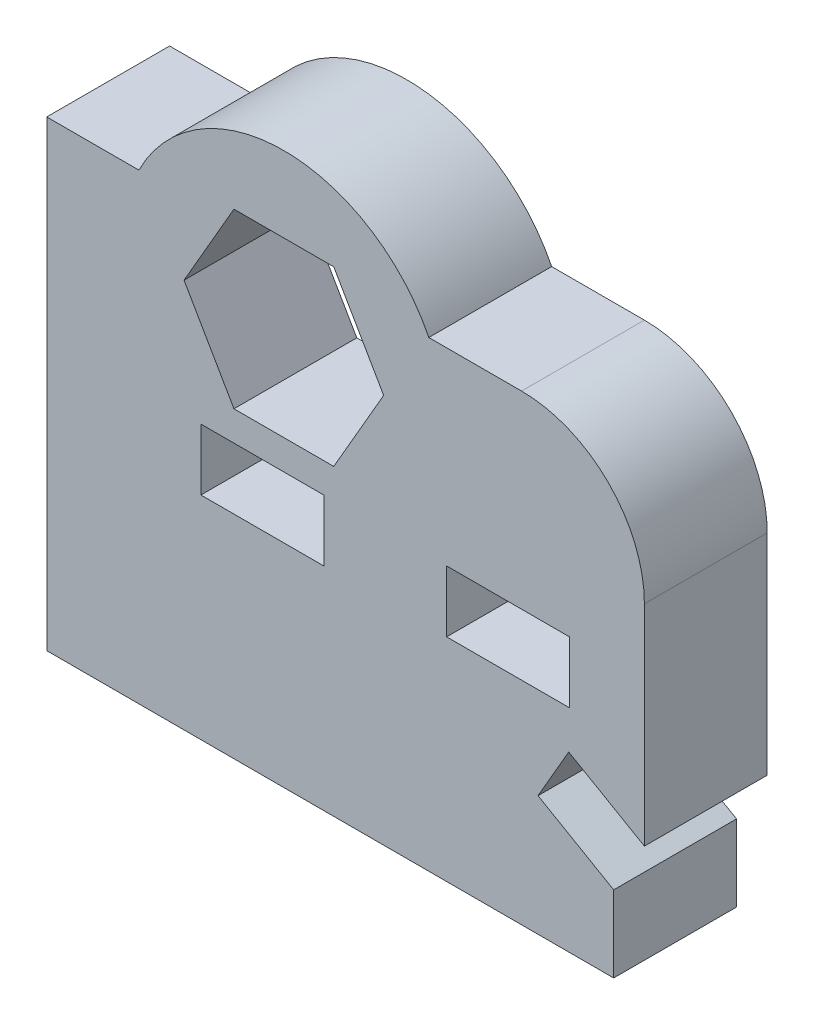
SolidWorks part; units mm, degrees
ref_plane "Front Plane" through (0, 0, 0) normal (0, 0, 1) x (1, 0, 0)
ref_plane "Top Plane" through (0, 0, 0) normal (0, 1, 0) x (1, 0, 0)
ref_plane "Right Plane" through (0, 0, 0) normal (1, 0, 0) x (0, 0, -1)
sketch "Sketch1" plane through (0, 0, 0) normal (0, 0, 1) x (1, 0, 0)
  line L0 (14.4756, 6) -> (15.4756, 7.7321)
  line L1 (3.5, 8.9911) -> (3.5, 10.9911)
  line L2 (16.9397, 2.0911) -> (-1.5203, 2.0911)
  line L3 (-1.5203, 17.1426) -> (-1.5203, 2.0911)
  line L4 (17.9397, 13.1426) -> (17.9397, 6.3094)
  line L5 (1.4797, 17.1426) -> (-1.5203, 17.1426)
  line L6 (7.825, 11.96) -> (4.575, 17.5892) construction
  line L7 (16.9397, 4.5774) -> (16.9397, 2.0911)
  line L8 (7.5, 8.9911) -> (7.5, 10.9911)
  line L9 (3.5, 8.9911) -> (7.5, 8.9911)
  line L10 (15.4756, 7.7321) -> (17.9397, 6.3094)
  line L11 (3.5, 10.9911) -> (7.5, 10.9911)
  line L12 (14.4756, 6) -> (16.9397, 4.5774)
  line L13 (11.5, 8.9911) -> (11.5, 10.9911)
  line L14 (11.5, 8.9911) -> (15.5, 8.9911)
  line L15 (15.5, 8.9911) -> (15.5, 10.9911)
  line L16 (11.5, 10.9911) -> (15.5, 10.9911)
  line L17 (7.825, 17.5892) -> (4.575, 11.96) construction
  line L19 (13.9397, 17.1426) -> (10.9203, 17.1426)
  line L20 (2.95, 14.7746) -> (4.575, 11.96)
  line L21 (4.575, 11.96) -> (7.825, 11.96)
  line L22 (7.825, 11.96) -> (9.45, 14.7746)
  line L23 (9.45, 14.7746) -> (7.825, 17.5892)
  line L24 (7.825, 17.5892) -> (4.575, 17.5892)
  line L25 (4.575, 17.5892) -> (2.95, 14.7746)
  arc A0 (17.9397, 13.1426) -> (13.9397, 17.1426) centre (13.9397, 13.1426) ccw
  arc A1 (10.9203, 17.1426) -> (1.4797, 17.1426) centre (6.2, 14.7746) ccw
  dimension "D1" = 4
  dimension "D2" = 18.46
  dimension "D4" = 3.25
  dimension "D5" = 3.5
  dimension "D13" = 11.5
  dimension "D14" = 14.4756
  dimension "D15" = 15.4756
  dimension "D18" = 4.5774
  dimension "D19" = 8.9911
extrude "Boss-Extrude1" add sketch "Sketch1" along normal blind 4
